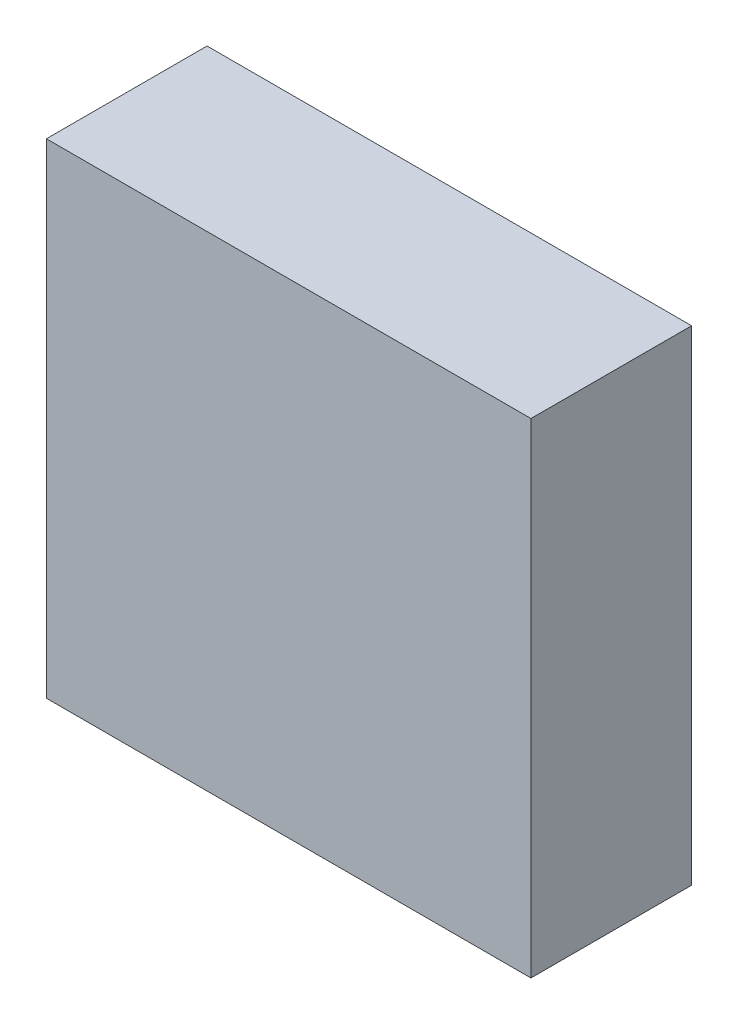
SolidWorks part; units mm, degrees
ref_plane "Front" through (0, 0, 0) normal (0, 0, 1) x (1, 0, 0)
ref_plane "Top" through (0, 0, 0) normal (0, 1, 0) x (1, 0, 0)
ref_plane "Right" through (0, 0, 0) normal (1, 0, 0) x (0, 0, -1)
sketch "Sketch1" plane through (0, 0, 0) normal (0, 0, 1) x (1, 0, 0)
  line L1 (-4.75, -4.75) -> (4.75, -4.75)
  line L2 (-4.75, -4.75) -> (-4.75, 4.75)
  line L3 (-4.75, 4.75) -> (4.75, 4.75)
  line L4 (4.75, -4.75) -> (4.75, 4.75)
  line L5 (-4.75, -4.75) -> (4.75, 4.75) construction
  line L6 (-4.75, 4.75) -> (4.75, -4.75) construction
  point P0 (0, 0)
  dimension "D1" = 9.5
  dimension "D2" = 9.5
extrude "Boss-Extrude1" add sketch "Sketch1" along normal mid plane 3.15
